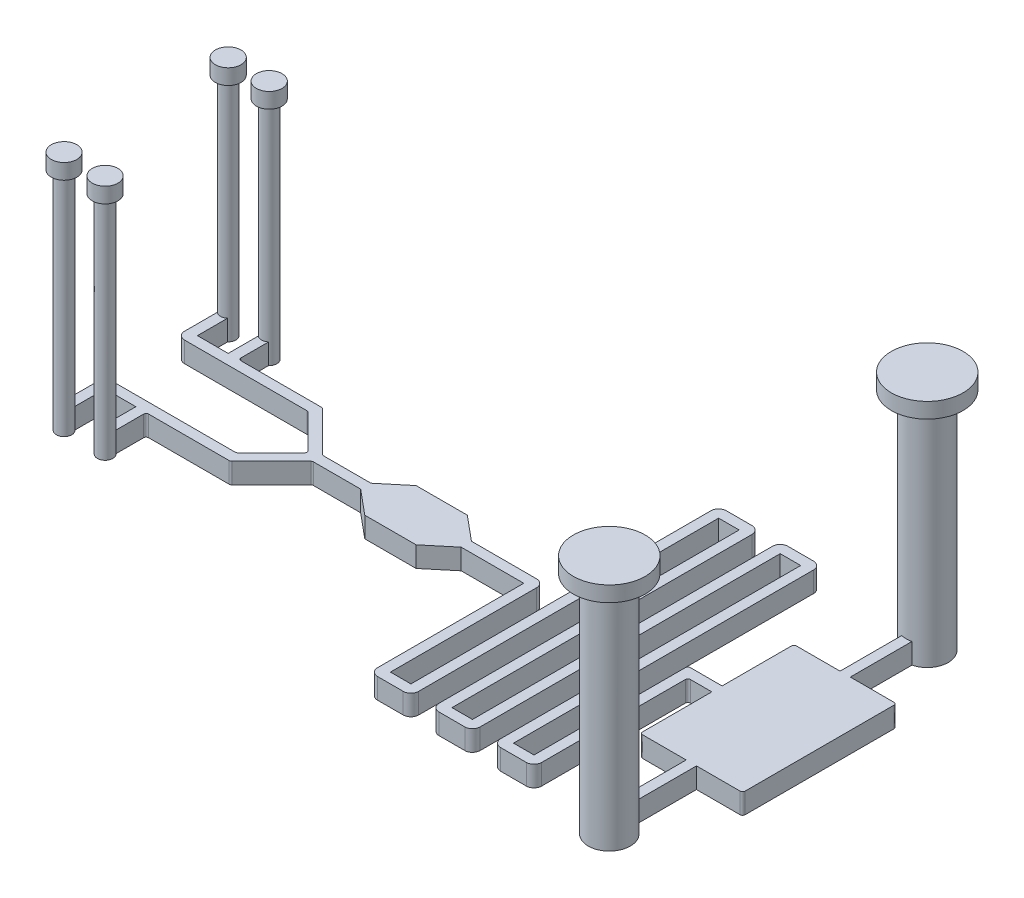
SolidWorks part; units mm, degrees
ref_plane "Front Plane" through (0, 0, 0) normal (0, 0, 1) x (1, 0, 0)
ref_plane "Top Plane" through (0, 0, 0) normal (0, 1, 0) x (1, 0, 0)
ref_plane "Right Plane" through (0, 0, 0) normal (1, 0, 0) x (0, 0, -1)
sketch "skelton_drawing" plane through (0, 0, 0) normal (0, 1, 0) x (1, 0, 0)
  line L0 (0, 0) -> (1.8251, 0) construction
  line L1 (15.1638, 7.25) -> (15.1638, -7.25)
  line L2 (14.9138, 7.5) -> (10.6638, 7.5)
  line L3 (14.9138, -7.5) -> (10.6638, -7.5)
  line L4 (5.1638, 7.25) -> (5.1638, 0.5)
  line L5 (5.1638, -0.5) -> (5.1638, -7.25)
  line L6 (9.6638, 7.5) -> (5.4138, 7.5)
  line L8 (5.1638, 0) -> (15.1638, 0) construction
  line L9 (9.6638, -7.5) -> (5.4138, -7.5)
  line L13 (9.6638, -7.5) -> (9.6638, -15.5) construction
  line L14 (10.1638, -7.5) -> (10.1638, -15.5) construction
  line L15 (10.6638, -7.5) -> (10.6638, -15.5) construction
  line L16 (9.6638, 7.5) -> (9.6638, 15.5) construction
  line L17 (10.1638, 7.5) -> (10.1638, 15.5) construction
  line L19 (-21.6749, 2.5) -> (-26.6749, 2.5)
  line L20 (-21.6749, -2.5) -> (-26.6749, -2.5)
  line L22 (10.6638, 7.5) -> (10.6638, 15.5) construction
  line L24 (-26.6749, 2.5) -> (-29.0749, 0.5)
  line L25 (-29.0749, -0.5) -> (-26.6749, -2.5)
  line L26 (-19.2749, -0.5) -> (-21.6749, -2.5)
  line L27 (-21.6749, 2.5) -> (-19.2749, 0.5)
  line L28 (-33.8585, 0.5732) -> (-37.7121, 4.4268)
  line L39 (10.1638, 13.45) -> (10.1638, 15.5) construction
  line L40 (10.1638, -7.5) -> (10.1638, -13.45) construction
  line L41 (-0.1749, -14.5) -> (-0.1749, 14.75)
  line L42 (5.1638, 0.5) -> (2.0751, 0.5)
  line L43 (1.8251, 0.25) -> (1.8251, -14.5)
  line L44 (1.8251, -14.5) -> (-0.1749, -14.5)
  line L45 (-1.1749, -14.75) -> (-1.1749, 14.5)
  line L46 (5.1638, -0.5) -> (3.0751, -0.5)
  line L47 (2.8251, -0.75) -> (2.8251, -14.75)
  line L48 (2.0751, -15.5) -> (-0.4249, -15.5)
  line L49 (-0.9249, 15.5) -> (-3.4249, 15.5)
  line L50 (-4.1749, 14.75) -> (-4.1749, -14.5)
  line L51 (-4.1749, -14.5) -> (-6.1749, -14.5)
  line L52 (-6.1749, -14.5) -> (-6.1749, 14.75)
  line L53 (-6.9249, 15.5) -> (-9.4249, 15.5)
  line L54 (-10.1749, 14.75) -> (-10.1749, -14.5)
  line L55 (-10.1749, -14.5) -> (-12.1749, -14.5)
  line L57 (-19.2749, -0.5) -> (-13.1749, -0.5)
  line L58 (-1.1749, 14.5) -> (-3.1749, 14.5)
  line L59 (-3.1749, 14.5) -> (-3.1749, -14.75)
  line L60 (-3.9249, -15.5) -> (-6.4249, -15.5)
  line L61 (-7.1749, -14.75) -> (-7.1749, 14.5)
  line L62 (-7.1749, 14.5) -> (-9.1749, 14.5)
  line L63 (-9.1749, 14.5) -> (-9.1749, -14.75)
  line L64 (-9.9249, -15.5) -> (-12.4249, -15.5)
  line L65 (-13.1749, -14.75) -> (-13.1749, -0.5)
  line L66 (-19.2749, 0.5) -> (-12.9249, 0.5)
  line L67 (-37.8889, 4.5) -> (-45.7424, 4.5)
  line L68 (-29.0749, 0.5) -> (-33.6818, 0.5)
  line L69 (-34.8763, -0.1768) -> (-38.1263, -3.4268)
  line L70 (-38.3031, -3.5) -> (-50.2424, -3.5)
  line L71 (-49.9924, -4.5) -> (-49.9924, -7.441)
  line L72 (-49.9924, -4.5) -> (-46.9924, -4.5)
  line L73 (-46.9924, -4.5) -> (-46.9924, -7.441)
  line L74 (-45.9924, 4.75) -> (-45.9924, 7.441)
  line L75 (-50.9924, 4.25) -> (-50.9924, 7.441)
  line L76 (-50.2424, 3.5) -> (-46.2424, 3.5)
  line L77 (9.6638, -7.5) -> (9.6638, -13.5119)
  line L78 (10.6638, 7.5) -> (10.6638, 13.5119)
  line L79 (-34.8763, 0.1768) -> (-38.1263, 3.4268)
  line L80 (-38.3031, 3.5) -> (-46.2424, 3.5)
  line L81 (-29.0749, -0.5) -> (-33.6818, -0.5)
  line L82 (-33.8585, -0.5732) -> (-37.7121, -4.4268)
  line L83 (-37.8889, -4.5) -> (-45.7424, -4.5)
  line L84 (-50.9924, -4.25) -> (-50.9924, -7.441)
  line L86 (-45.9924, -4.75) -> (-45.9924, -7.441)
  line L87 (-46.9924, 4.5) -> (-46.9924, 7.441)
  line L88 (-49.9924, 4.5) -> (-49.9924, 7.441)
  line L89 (-49.9924, 4.5) -> (-46.9924, 4.5)
  line L90 (10.6638, -7.5) -> (10.6638, -13.5119)
  line L91 (9.6638, 7.5) -> (9.6638, 13.5119)
  line L108 (-12.1749, -14.5) -> (-12.1749, -0.25)
  arc A0 (15.1638, 7.25) -> (14.9138, 7.5) centre (14.9138, 7.25) ccw
  arc A1 (5.4138, 7.5) -> (5.1638, 7.25) centre (5.4138, 7.25) ccw
  arc A2 (14.9138, -7.5) -> (15.1638, -7.25) centre (14.9138, -7.25) ccw
  arc A3 (5.4138, -7.5) -> (5.1638, -7.25) centre (5.4138, -7.25) cw
  arc A4 (10.6638, 13.5119) -> (9.6638, 13.5119) centre (10.1638, 15.5) ccw
  arc A5 (-12.9249, 0.5) -> (-12.1749, -0.25) centre (-12.9249, -0.25) cw
  arc A6 (9.6638, -13.5119) -> (10.6638, -13.5119) centre (10.1638, -15.5) ccw
  arc A7 (-50.9924, -7.441) -> (-49.9924, -7.441) centre (-50.4924, -8) ccw
  arc A8 (-46.9924, -7.441) -> (-45.9924, -7.441) centre (-46.4924, -8) ccw
  arc A9 (-45.9924, 7.441) -> (-46.9924, 7.441) centre (-46.4924, 8) ccw
  arc A10 (-49.9924, 7.441) -> (-50.9924, 7.441) centre (-50.4924, 8) ccw
  arc A11 (1.8251, 0.25) -> (2.0751, 0.5) centre (2.0751, 0.25) cw
  arc A12 (2.8251, -0.75) -> (3.0751, -0.5) centre (3.0751, -0.75) cw
  arc A13 (-45.7424, 4.5) -> (-45.9924, 4.75) centre (-45.7424, 4.75) cw
  arc A14 (-45.9924, -4.75) -> (-45.7424, -4.5) centre (-45.7424, -4.75) cw
  arc A15 (-37.8889, -4.5) -> (-37.7121, -4.4268) centre (-37.8889, -4.25) ccw
  arc A16 (-38.1263, -3.4268) -> (-38.3031, -3.5) centre (-38.3031, -3.25) cw
  arc A17 (-37.7121, 4.4268) -> (-37.8889, 4.5) centre (-37.8889, 4.25) ccw
  arc A18 (-38.1263, 3.4268) -> (-38.3031, 3.5) centre (-38.3031, 3.25) ccw
  arc A19 (-0.9249, 15.5) -> (-0.1749, 14.75) centre (-0.9249, 14.75) cw
  arc A20 (-3.4249, 15.5) -> (-4.1749, 14.75) centre (-3.4249, 14.75) ccw
  arc A21 (-33.8585, -0.5732) -> (-33.6818, -0.5) centre (-33.6818, -0.75) cw
  arc A22 (-33.6818, 0.5) -> (-33.8585, 0.5732) centre (-33.6818, 0.75) cw
  arc A23 (-6.9249, 15.5) -> (-6.1749, 14.75) centre (-6.9249, 14.75) cw
  arc A24 (-10.1749, 14.75) -> (-9.4249, 15.5) centre (-9.4249, 14.75) cw
  arc A25 (-34.8763, 0.1768) -> (-34.8763, -0.1768) centre (-35.0531, 0) cw
  arc A28 (2.0751, -15.5) -> (2.8251, -14.75) centre (2.0751, -14.75) ccw
  arc A31 (-3.1749, -14.75) -> (-3.9249, -15.5) centre (-3.9249, -14.75) cw
  arc A32 (-6.4249, -15.5) -> (-7.1749, -14.75) centre (-6.4249, -14.75) cw
  arc A35 (-9.1749, -14.75) -> (-9.9249, -15.5) centre (-9.9249, -14.75) cw
  arc A36 (-12.4249, -15.5) -> (-13.1749, -14.75) centre (-12.4249, -14.75) cw
  arc A37 (-0.4249, -15.5) -> (-1.1749, -14.75) centre (-0.4249, -14.75) cw
  arc A40 (-50.2424, 3.5) -> (-50.9924, 4.25) centre (-50.2424, 4.25) cw
  arc A41 (-50.2424, -3.5) -> (-50.9924, -4.25) centre (-50.2424, -4.25) ccw
  point P6 (15.1638, 0)
  point P14 (2.3251, 0)
  point P46 (15.1638, 7.5)
  point P51 (15.1638, -7.5)
  point P56 (-50.4924, -4)
  point P65 (-50.4924, 4)
  point P70 (-9.6749, 15)
  point P73 (-6.6749, 15)
  point P76 (-3.6749, 15)
  point P79 (-0.6749, 15)
  point P82 (-0.6749, -15)
  point P85 (-6.6749, -15)
  point P88 (-12.6749, -15)
  point P91 (-9.6749, -15)
  point P94 (-3.6749, -15)
  point P97 (2.3251, -15)
  dimension "D17" = 0.25
  dimension "D7" = 4.1
  dimension "D11" = 4.1
  dimension "D12" = 1.5
  dimension "D13" = 1.5
  dimension "D14" = 1.5
  dimension "D15" = 1.5
  dimension "D18" = 0.25
  dimension "D19" = 0.25
  dimension "D1" = 15
  dimension "D2" = 3
  dimension "D3" = 3
  dimension "D4" = 3
  dimension "D5" = 3
  dimension "D6" = 3
  dimension "D8" = 5
  dimension "D9" = 5
  dimension "D10" = 5
  dimension "D16" = 8
  dimension "D22" = 0.5
  dimension "D23" = 0.5
extrude "Skelton_base" add sketch "skelton_drawing" along normal blind 2
sketch "Sketch3" plane through (0, 2, 0) normal (0, 1, 0) x (1, 0, 0)
  circle A0 centre (10.1638, 15.5) radius 2.05
  circle A1 centre (10.1638, -15.5) radius 2.05
  circle A2 centre (-46.4924, 8) radius 0.75
  circle A3 centre (-50.4924, 8) radius 0.75
  circle A4 centre (-46.4924, -8) radius 0.75
  circle A5 centre (-50.4924, -8) radius 0.75
extrude "Support_leg" add sketch "Sketch3" along normal blind 20
sketch "Sketch5" plane through (0, 22, 0) normal (0, 1, 0) x (1, 0, 0)
  circle A0 centre (10.1638, -15.5) radius 3.5
  circle A1 centre (10.1638, 15.5) radius 3.5
  circle A2 centre (-46.4924, 8) radius 1.25
  circle A3 centre (-50.4924, 8) radius 1.25
  circle A4 centre (-46.4924, -8) radius 1.25
  circle A5 centre (-50.4924, -8) radius 1.2475
  dimension "D1" = 2.4951
  dimension "D2" = 2.5
  dimension "D3" = 2.5
  dimension "D4" = 2.5
  dimension "D5" = 7
  dimension "D6" = 7
extrude "Support_head" add sketch "Sketch5" along normal blind 1.5
